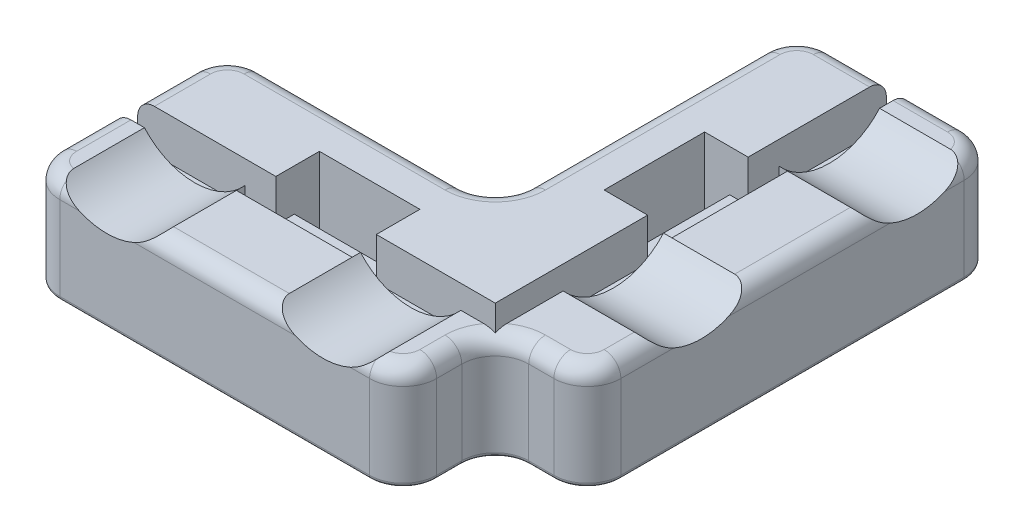
SolidWorks part; units mm, degrees
ref_plane "Спереди" through (0, 0, 0) normal (0, 0, 1) x (1, 0, 0)
ref_plane "Сверху" through (0, 0, 0) normal (0, 1, 0) x (1, 0, 0)
ref_plane "Справа" through (0, 0, 0) normal (1, 0, 0) x (0, 0, -1)
sketch "Эскиз1" plane through (0, 0, 0) normal (0, 1, 0) x (1, 0, 0)
  line L9 (4, 0) -> (41, 0)
  line L10 (0, 4) -> (0, 20)
  line L11 (4, 24) -> (28, 24)
  line L12 (45, 4) -> (45, 7)
  line L17 (36, 60) -> (52, 60)
  line L18 (32, 56) -> (32, 28)
  line L19 (49, 11) -> (52, 11)
  line L20 (56, 56) -> (56, 15)
  arc A0 (52, 11) -> (56, 15) centre (52, 15) ccw
  arc A1 (41, 0) -> (45, 4) centre (41, 4) ccw
  arc A2 (36, 60) -> (32, 56) centre (36, 56) ccw
  arc A3 (52, 60) -> (56, 56) centre (52, 56) cw
  arc A4 (0, 20) -> (4, 24) centre (4, 20) cw
  arc A5 (4, 0) -> (0, 4) centre (4, 4) cw
  arc A6 (49, 11) -> (45, 7) centre (49, 7) ccw
  arc A7 (28, 24) -> (32, 28) centre (28, 28) ccw
  point P15 (56, 11)
  point P18 (45, 0)
  point P23 (56, 60)
  point P26 (0, 24)
  point P30 (0, 0)
  dimension "D3" = 49
  dimension "D4" = 11
  dimension "D6" = 4
  dimension "D1" = 24
  dimension "D2" = 45
  dimension "D5" = 11
extrude "Тело" add sketch "Эскиз1" along normal blind 12.5
sketch "Эскиз6" plane through (0, 0, 0) normal (0, -1, 0) x (1, 0, 0)
  line L0 (4, -24) -> (28, -24) construction
  line L1 (32, -56) -> (32, -28) construction
  circle A0 centre (4, -4) radius 1
  circle A1 centre (41, -4) radius 1
  circle A2 centre (52, -15) radius 1
  circle A3 centre (4, -20) radius 1
  circle A4 centre (36, -56) radius 1
  circle A5 centre (52, -56) radius 1
  circle A6 centre (34, -22) radius 1
  dimension "D1" = 2
  dimension "D2" = 2
  dimension "D3" = 2
extrude "Крепеж" cut sketch "Эскиз6" against normal blind 7
fillet "Скругление1" radius 2 16 edges at (1.1716, 12.5, -1.1716) (0, 12.5, -12) (1.1716, 12.5, -22.8284) (16, 12.5, -24) (30.8284, 12.5, -25.1716) (32, 12.5, -42) (33.1716, 12.5, -58.8284) (44, 12.5, -60) (54.8284, 12.5, -58.8284) (56, 12.5, -35.5) (54.8284, 12.5, -12.1716) (50.5, 12.5, -11) (46.1716, 12.5, -9.8284) (45, 12.5, -5.5) (43.8284, 12.5, -1.1716) (22.5, 12.5, 0)
sketch "Эскиз7" plane through (0, 12.5, 0) normal (0, 1, 0) x (1, 0, 0)
  line L0 (4, 2) -> (41, 2) construction
  line L1 (16.5, 18.5) -> (28.5, 18.5)
  line L2 (16.5, 18.5) -> (16.5, 15.5)
  line L3 (16.5, 15.5) -> (28.5, 15.5)
  line L4 (28.5, 18.5) -> (28.5, 15.5)
  line L5 (56, 56) -> (56, 15) construction
  line L6 (37.5, 43.5) -> (40.5, 43.5)
  line L7 (37.5, 43.5) -> (37.5, 31.5)
  line L8 (37.5, 31.5) -> (40.5, 31.5)
  line L9 (40.5, 43.5) -> (40.5, 31.5)
  line L10 (52, 11) -> (49, 11) construction
  point P4 (16.5, 17)
  point P8 (22.5, 15.5)
  point P9 (22.5, 2)
  point P14 (39, 31.5)
  point P17 (40.5, 37.5)
  dimension "D1" = 3
  dimension "D2" = 12
  dimension "D3" = 17
  dimension "D4" = 17
  dimension "D5" = 26.5
extrude "Вырез-Вытянуть1" cut sketch "Эскиз7" against normal through all and the other way through all
sketch "Эскиз8" plane through (0, 12.5, 0) normal (0, 1, 0) x (1, 0, 0)
  line L0 (16.5, 18.5) -> (16.5, 15.5) construction
  line L1 (0, 13.3) -> (16.5, 13.3)
  line L2 (0, 13.3) -> (0, 10.5)
  line L3 (0, 10.5) -> (45.5, 10.5)
  line L6 (37.5, 31.5) -> (40.5, 31.5) construction
  line L7 (42.7, 61) -> (45.5, 61)
  line L8 (42.7, 61) -> (42.7, 43.5)
  line L10 (45.5, 61) -> (45.5, 10.5)
  line L11 (40.5, 31.5) -> (40.5, 43.5) construction
  line L12 (28.5, 15.5) -> (28.5, 18.5) construction
  line L14 (16.5, 13.3) -> (16.5, 15.5)
  line L15 (16.5, 15.5) -> (28.5, 15.5)
  line L16 (28.5, 13.3) -> (28.5, 15.5)
  line L17 (40.5, 43.5) -> (37.5, 43.5) construction
  line L18 (42.7, 43.5) -> (40.5, 43.5)
  line L20 (42.7, 31.5) -> (40.5, 31.5)
  line L21 (40.5, 43.5) -> (40.5, 31.5)
  line L22 (28.5, 13.3) -> (42.7, 13.3)
  line L23 (42.7, 31.5) -> (42.7, 13.3)
  line L24 (0, 4) -> (0, 20) construction
  point P4 (16.5, 17)
  point P7 (39, 31.5)
  point P8 (40.5, 37.5)
  point P22 (40.5, 37.5)
  dimension "D1" = 6.5
  dimension "D2" = 45.5
  dimension "D3" = 2.8
  dimension "D4" = 6.5
  dimension "D5" = 17.5
extrude "Вырез-Вытянуть2" cut sketch "Эскиз8" against normal offset from surface (5 mm away) 7.5 up to face at (22.5, 0, -17)
sketch "Эскиз9" plane through (0, 0, 0) normal (0, 0, 1) x (1, 0, 0)
  line L0 (4, 0) -> (41, 0) construction
  line L1 (45.5, 7.5) -> (0, 7.5) construction
  circle A0 centre (9.6, 17.8) radius 8
  circle A1 centre (35.4, 17.8) radius 8
  point P7 (22.5, 0)
  dimension "D1" = 16
  dimension "D2" = 12.9
  dimension "D3" = 12.9
  dimension "D4" = 10.3
extrude "Вырез-Вытянуть3" cut sketch "Эскиз9" against normal up to surface (13.3 mm away) up to face at (6.9172, 10.1828, -13.3)
sketch "Эскиз10" plane through (56, 0, 0) normal (1, 0, 0) x (0, 0, -1)
  line L2 (43.5, 12.5) -> (31.5, 12.5) construction
  line L3 (60, 7.5) -> (10.5, 7.5) construction
  circle A0 centre (24.6, 17.8) radius 8
  circle A1 centre (50.4, 17.8) radius 8
  point P7 (37.5, 12.5)
  dimension "D1" = 16
  dimension "D2" = 12.9
  dimension "D3" = 12.9
  dimension "D4" = 10.3
extrude "Вырез-Вытянуть4" cut sketch "Эскиз10" against normal up to surface (13.3 mm away) up to face at (42.7, 10, -22.4)
sketch "Эскиз11" plane through (0, 12.5, 0) normal (0, 1, 0) x (1, 0, 0)
  line L1 (15.5925, 10.5) -> (29.4075, 10.5)
  line L2 (15.5925, 10.5) -> (15.5925, 9.5)
  line L3 (15.5925, 9.5) -> (29.4075, 9.5)
  line L4 (29.4075, 10.5) -> (29.4075, 9.5)
  line L7 (45.5, 44.4075) -> (46.5, 44.4075)
  line L8 (45.5, 44.4075) -> (45.5, 30.5925)
  line L9 (45.5, 30.5925) -> (46.5, 30.5925)
  line L10 (46.5, 44.4075) -> (46.5, 30.5925)
  line L12 (29.4075, 10.5) -> (29.4075, 2) construction
  point P4 (15.7925, 10.5)
  point P5 (29.4075, 10.5)
  point P6 (45.5, 44.5075)
  point P9 (45.5, 30.8925)
  point P15 (45.5, 27.4929)
  point P19 (0, 0)
  dimension "D1" = 1
extrude "Вырез-Вытянуть7" cut sketch "Эскиз11" against normal up to surface (5 mm away) up to face at (30.9143, 7.5, -26.8)
fillet "Скругление2" radius 0.5 31 edges at (40.5, 0, -37.5) (39, 0, -31.5) (37.5, 0, -37.5) (39, 0, -43.5) (28.5, 0, -17) (22.5, 0, -15.5) (16.5, 0, -17) (22.5, 0, -18.5) (56, 0, -35.5) (54.8284, 0, -58.8284) (44, 0, -60) (33.1716, 0, -58.8284) (32, 0, -42) (30.8284, 0, -25.1716) (16, 0, -24) (1.1716, 0, -22.8284) (0, 0, -12) (1.1716, 0, -1.1716) (22.5, 0, 0) (43.8284, 0, -1.1716) (45, 0, -5.5) (46.1716, 0, -9.8284) (50.5, 0, -11) (54.8284, 0, -12.1716) (4, 0, -5) (36, 0, -57) (34, 0, -23) (52, 0, -57) (4, 0, -21) (52, 0, -16) (41, 0, -5)
